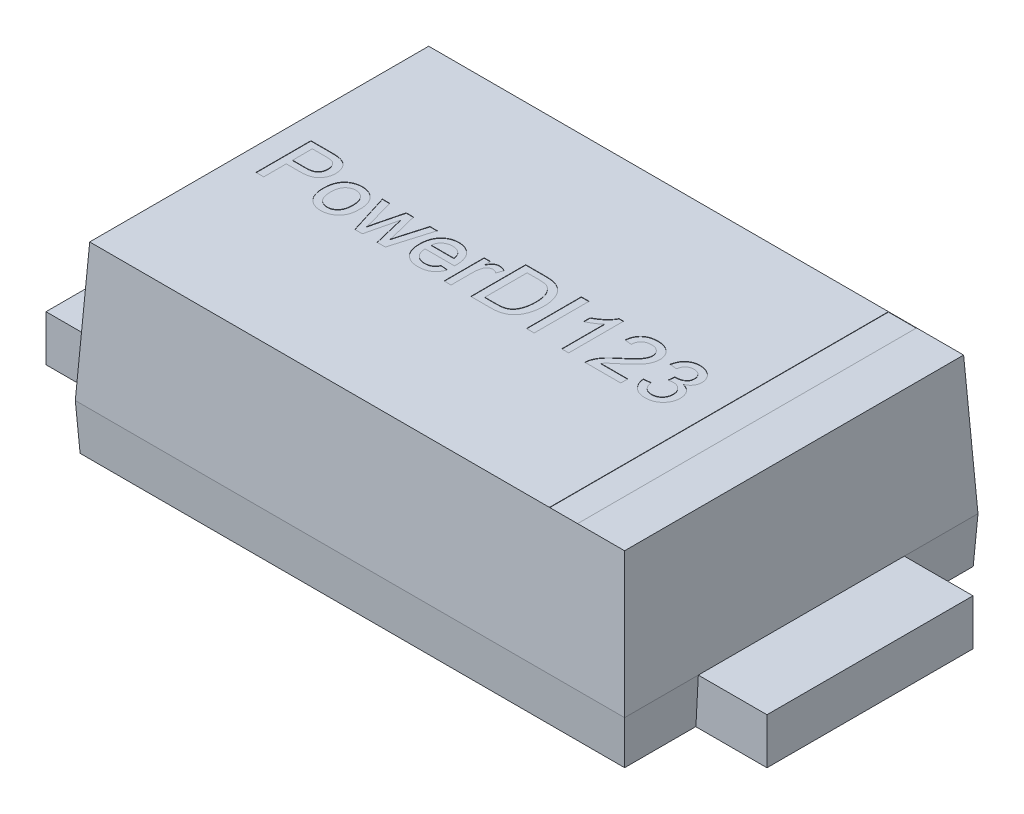
SolidWorks part; units mm, degrees
ref_plane "Front" through (0, 0, 0) normal (0, 0, 1) x (1, 0, 0)
ref_plane "Top" through (0, 0, 0) normal (0, 1, 0) x (1, 0, 0)
ref_plane "Right" through (0, 0, 0) normal (1, 0, 0) x (0, 0, -1)
ref_plane "Plane1" through (0, 0.25, 0) normal (0, 1, 0) x (1, 0, 0)
sketch "Sketch1" plane through (0, 0.25, 0) normal (0, 1, 0) x (1, 0, 0)
  line L0 (0, 0) -> (0, 23.5773) construction
  line L1 (0, 0) -> (7.5602, 0) construction
  line L2 (1.5, -0.965) -> (1.5, 0.965)
  line L3 (-1.5, -0.965) -> (-1.5, 0.965)
  line L4 (-1.5, -0.965) -> (1.5, -0.965)
  line L5 (-1.5, 0.965) -> (1.5, 0.965)
  line L6 (0, 0.965) -> (7.5602, 0.965) construction
  line L7 (0, -0.965) -> (7.5602, -0.965) construction
  line L8 (-1.5, 0) -> (-1.5, 23.5773) construction
  line L9 (1.5, 0) -> (1.5, 23.5773) construction
  dimension "D1" = 1.5
  dimension "D2" = 1.5
  dimension "D3" = 0.965
  dimension "D4" = 0.965
extrude "Boss-Extrude1" add sketch "Sketch1" along normal blind 0.75 draft 3
sketch "Sketch5" plane through (0, 0.25, 0) normal (0, -1, 0) x (1, 0, 0)
  line L4 (1.5, 0.965) -> (-1.5, 0.965)
  line L5 (-1.5, 0.965) -> (-1.5, -0.965)
  line L6 (-1.5, -0.965) -> (1.5, -0.965)
  line L7 (1.5, -0.965) -> (1.5, 0.965)
  line L8 (1.5, 0.965) -> (-1.5, 0.965)
  line L9 (-1.5, 0.965) -> (-1.5, -0.965)
  line L10 (-1.5, -0.965) -> (1.5, -0.965)
  line L11 (1.5, -0.965) -> (1.5, 0.965)
  dimension "D1" = 0
extrude "Boss-Extrude3" add sketch "Sketch5" along normal blind 0.25 draft 3
sketch "Sketch6" plane through (0, 0, 0) normal (0, -1, 0) x (1, 0, 0)
  line L0 (0, 0) -> (0, 1.1557) construction
  line L1 (0, 0) -> (1.6845, 0) construction
  line L2 (1.5, -0.965) -> (-1.5, -0.965) construction
  line L3 (-1.5, 0.965) -> (1.5, 0.965) construction
  line L4 (-1.5, -0.965) -> (-1.5, 0.965) construction
  line L5 (1.5, 0.965) -> (1.5, -0.965) construction
  line L6 (1.5, -0.965) -> (-1.5, -0.965) construction
  line L7 (-1.5, 0.965) -> (1.5, 0.965) construction
  line L8 (-1.5, -0.965) -> (-1.5, 0.965) construction
  line L9 (1.5, 0.965) -> (1.5, -0.965) construction
  line L10 (-1.375, -0.965) -> (-1.375, 0.965) construction
  line L12 (0.025, -0.625) -> (1.225, -0.625)
  line L13 (0.025, 0.625) -> (1.225, 0.625)
  line L14 (0.025, 0.625) -> (0.025, -0.625)
  line L15 (1.225, -0.5625) -> (1.225, -0.625)
  line L16 (1.225, -0.5625) -> (1.875, -0.5625)
  line L17 (1.225, 0.5625) -> (1.875, 0.5625)
  line L18 (1.875, 0.5625) -> (1.875, -0.5625)
  line L19 (0, 0.5625) -> (1.6845, 0.5625) construction
  line L20 (0, -0.5625) -> (1.6845, -0.5625) construction
  line L21 (1.225, 0.625) -> (1.225, 0.5625)
  line L23 (-2, -0.625) -> (-2, 0.625)
  line L25 (-2, 0.625) -> (-1.225, 0.625)
  line L27 (-1.225, -0.625) -> (-2, -0.625)
  line L28 (-1.225, -0.625) -> (-1.225, 0.625)
  line L29 (-2, -0.965) -> (-2, 0.965) construction
  line L30 (1.225, 0.965) -> (1.225, -0.965) construction
  line L31 (-1.225, -0.965) -> (-1.225, 0.965) construction
  point P10 (1.375, 0.965)
  point P11 (1.375, -0.965)
  point P13 (1.6845, -0.625)
  point P15 (1.6845, 0.625)
  dimension "D3" = 0.625
  dimension "D9" = 1.25
  dimension "D10" = 1.125
  dimension "D13" = 0.625
  dimension "D1" = 0.125
  dimension "D4" = 0.5625
  dimension "D6" = 0.5625
  dimension "D8" = 0.5
  dimension "D11" = 0.275
  dimension "D12" = 0.275
extrude "Boss-Extrude4" add sketch "Sketch6" against normal blind 0.25 and the other way blind 0.001
sketch "Sketch7" plane through (0, 1, 0) normal (0, 1, 0) x (1, 0, 0)
  line L0 (1.0503, -0.9257) -> (1.0503, 0.9257)
  line L1 (-1.4607, -0.9257) -> (1.4607, -0.9257) construction
  line L2 (1.4607, 0.9257) -> (-1.4607, 0.9257) construction
  line L3 (1.0503, 0.9257) -> (1.204, 0.9257)
  line L4 (1.204, 0.9257) -> (1.204, -0.9257)
  line L5 (1.204, -0.9257) -> (1.0503, -0.9257)
  text T0 "PowerDI123" font "Arial" height 0.3
extrude "Cut-Extrude1" cut sketch "Sketch7" against normal blind 0.002
